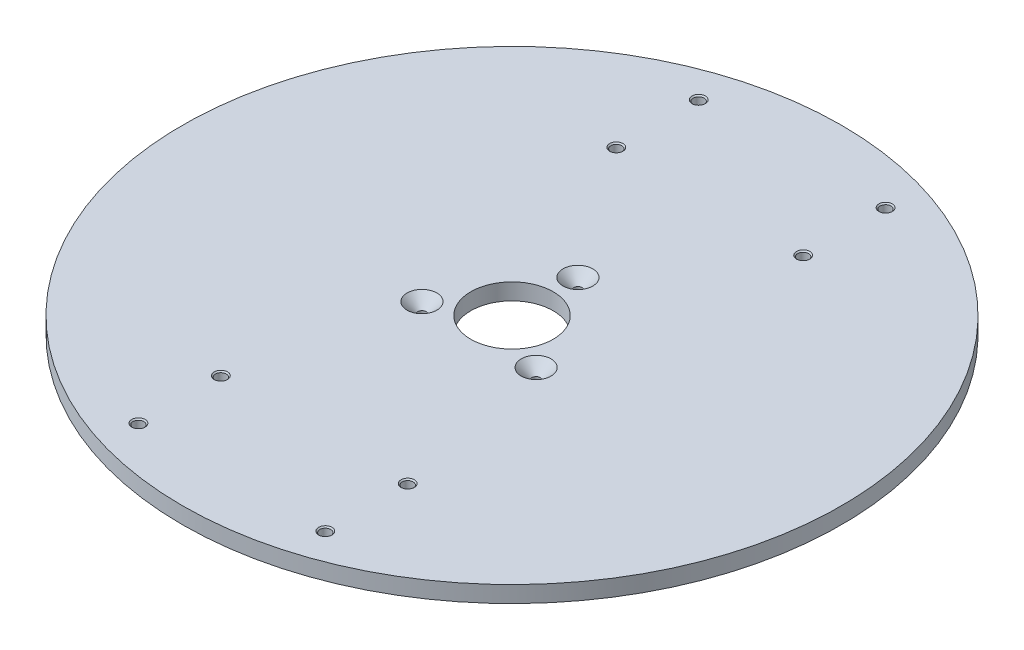
SolidWorks part; units mm, degrees
material "ABS"
ref_plane "前视基准面" through (0, 0, 0) normal (0, 0, 1) x (1, 0, 0)
ref_plane "上视基准面" through (0, 0, 0) normal (0, 1, 0) x (1, 0, 0)
ref_plane "右视基准面" through (0, 0, 0) normal (1, 0, 0) x (0, 0, -1)
sketch "草图1" plane through (0, 0, 0) normal (0, 1, 0) x (1, 0, 0)
  circle A0 centre (0, 0) radius 100
  dimension "D1" = 200
extrude "凸台-拉伸1" add sketch "草图1" along normal blind 5 contours A0
sketch "草图2" plane through (0, 5, 0) normal (0, 1, 0) x (1, 0, 0)
  circle A0 centre (0, 0) radius 20 construction
  dimension "D1" = 40
hole_wizard "M3 螺纹孔1" positions "草图3" profile "草图4" tap size "M3" standard "GB" end condition through all
sketch "草图3" plane through (0, 5, 0) normal (0, 1, 0) x (1, 0, 0)
  line L0 (0, 20) -> (0, 0) construction
  line L1 (0, 0) -> (17.3205, -10) construction
  line L3 (0, 0) -> (-17.3205, -10) construction
  circle A0 centre (0, 0) radius 20 construction
  point P0 (0, 20)
  point P6 (17.3205, -10)
  point P8 (-17.3205, -10)
  dimension "D1" = 120
  dimension "D2" = 120
sketch "草图4" plane through (0, 5, -20) normal (1, 0, 0) x (0, 0, 1)
  line L0 (0, 0) -> (0, 5)
  line L1 (0, 5) -> (1.25, 5)
  line L2 (1.25, 5) -> (1.25, 3.275)
  line L3 (1.25, 3.275) -> (4.525, 0)
  line L5 (4.525, 0) -> (0, 0)
  line L6 (-1.25, 3.275) -> (-4.525, 0) construction
  line L11 (0, -6.35) -> (0, 107.95) construction
  dimension "通孔螺纹孔钻头直径" = 2.5
  dimension "通孔螺纹孔钻头深度" = 5
  dimension "近端锥形沉头孔直径" = 9.05
  dimension "近端锥形沉头孔角度" = 90
cosmetic thread "孔螺纹线1" parameters "D2"=3
cosmetic thread "孔螺纹线2" parameters "D2"=3
cosmetic thread "孔螺纹线3" parameters "D2"=3
sketch "草图5" plane through (0, 5, 0) normal (0, 1, 0) x (1, 0, 0)
  circle A0 centre (0, 0) radius 12.5
  dimension "D1" = 25
extrude "切除-拉伸1" cut sketch "草图5" against normal through all
sketch "草图6" plane through (0, 5, 0) normal (0, 1, 0) x (1, 0, 0)
  line L1 (-33.35, -90) -> (33.35, -90) construction
  line L2 (-33.35, -90) -> (-33.35, 90) construction
  line L3 (-33.35, 90) -> (33.35, 90) construction
  line L4 (33.35, -90) -> (33.35, 90) construction
  line L5 (-33.35, -90) -> (33.35, 90) construction
  line L6 (-33.35, 90) -> (33.35, -90) construction
  line L7 (-28.35, -85) -> (28.35, -85) construction
  line L8 (-28.35, -85) -> (-28.35, 85) construction
  line L9 (-28.35, 85) -> (28.35, 85) construction
  line L10 (28.35, -85) -> (28.35, 85) construction
  line L11 (-28.35, -85) -> (28.35, 85) construction
  line L12 (-28.35, 85) -> (28.35, -85) construction
  line L14 (-28.35, -60) -> (28.35, -60)
  line L15 (-28.35, -60) -> (-28.35, 60)
  line L16 (-28.35, 60) -> (28.35, 60)
  line L17 (28.35, -60) -> (28.35, 60)
  line L18 (-28.35, -60) -> (28.35, 60) construction
  line L19 (-28.35, 60) -> (28.35, -60) construction
  point P0 (0, 0)
  point P5 (0, 0)
  point P12 (-28.35, 85)
  point P13 (28.35, 85)
  point P14 (28.35, -85)
  point P15 (-28.35, -85)
  point P16 (0, 0)
  point P26 (-28.35, 60)
  point P29 (28.35, 60)
  point P32 (-28.35, -60)
  point P35 (28.35, -60)
  dimension "D1" = 66.7
  dimension "D2" = 180
  dimension "D3" = 5
  dimension "D4" = 5
  dimension "D5" = 30
  dimension "D6" = 5
hole_wizard "M4 螺纹孔2" positions "草图6" profile "草图8" tap size "M4" standard "GB" end condition up to next
sketch "草图8" plane through (0, 5, 0) normal (1, 0, 0) x (0, 0, 1)
  line L0 (0, 0) -> (0, 5)
  line L1 (0, 5) -> (1.65, 5)
  line L2 (1.65, 5) -> (1.65, 0.375)
  line L3 (1.65, 0.375) -> (2.025, 0)
  line L5 (2.025, 0) -> (0, 0)
  line L6 (-1.65, 0.375) -> (-2.025, 0) construction
  line L11 (0, -6.35) -> (0, 107.95) construction
  dimension "通孔螺纹孔钻头直径" = 3.3
  dimension "通孔螺纹孔钻头深度" = 5
  dimension "近端锥形沉头孔直径" = 4.05
  dimension "近端锥形沉头孔角度" = 90
cosmetic thread "孔螺纹线8" parameters "D2"=4
cosmetic thread "孔螺纹线9" parameters "D2"=4
cosmetic thread "孔螺纹线10" parameters "D2"=4
cosmetic thread "孔螺纹线11" parameters "D2"=4
cosmetic thread "孔螺纹线12" parameters "D2"=4
cosmetic thread "孔螺纹线13" parameters "D2"=4
cosmetic thread "孔螺纹线14" parameters "D2"=4
cosmetic thread "孔螺纹线15" parameters "D2"=4
cosmetic thread "孔螺纹线16" parameters "D2"=4
cosmetic thread "孔螺纹线17" parameters "D2"=4
cosmetic thread "孔螺纹线18" parameters "D2"=4
cosmetic thread "孔螺纹线19" parameters "D2"=4
